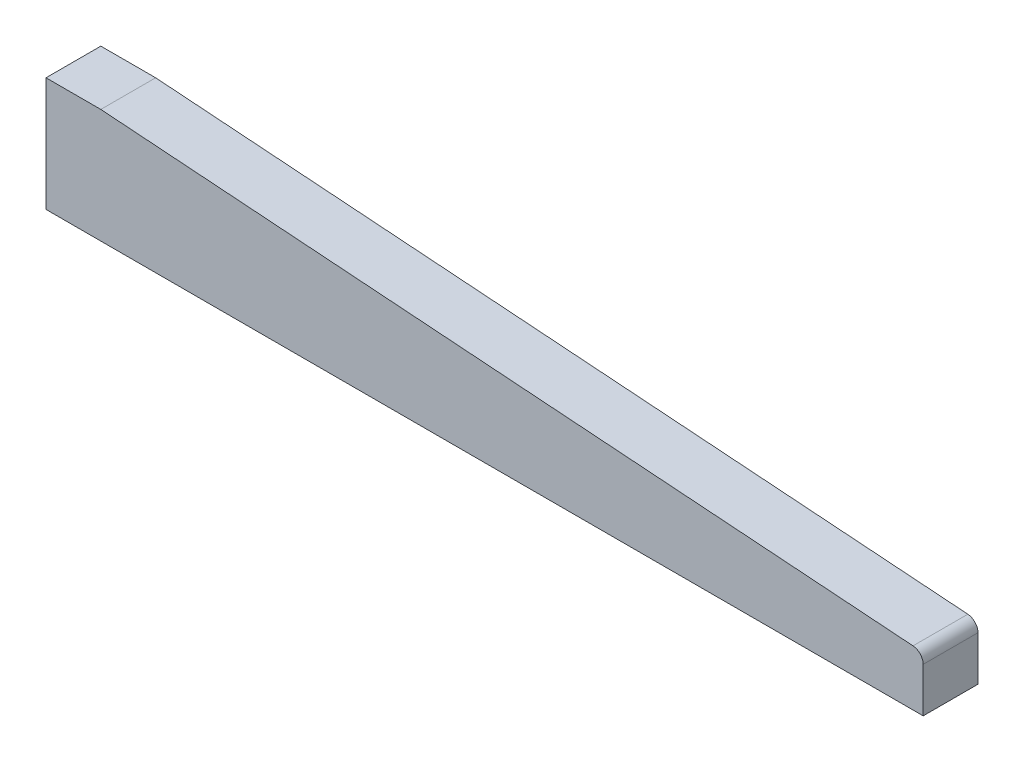
SolidWorks part; units mm, degrees
ref_plane "Front" through (0, 0, 0) normal (0, 0, 1) x (1, 0, 0)
ref_plane "Top" through (0, 0, 0) normal (0, 1, 0) x (1, 0, 0)
ref_plane "Right" through (0, 0, 0) normal (1, 0, 0) x (0, 0, -1)
sketch "Sketch1" plane through (0, 0, 0) normal (0, 0, 1) x (1, 0, 0)
  line L0 (0, 0) -> (0, 6.604)
  line L1 (0, 6.604) -> (3.175, 6.604)
  line L2 (3.175, 6.604) -> (50.8, 3.175)
  line L3 (50.8, 3.175) -> (50.8, 0)
  line L4 (50.8, 0) -> (0, 0)
  dimension "D1" = 3.175
  dimension "D2" = 6.604
  dimension "D3" = 50.8
  dimension "D4" = 3.175
extrude "Boss-Extrude1" add sketch "Sketch1" along normal mid plane 3.175
fillet "Fillet1" radius 0.635 1 edges at (50.8, 3.175, 0)
